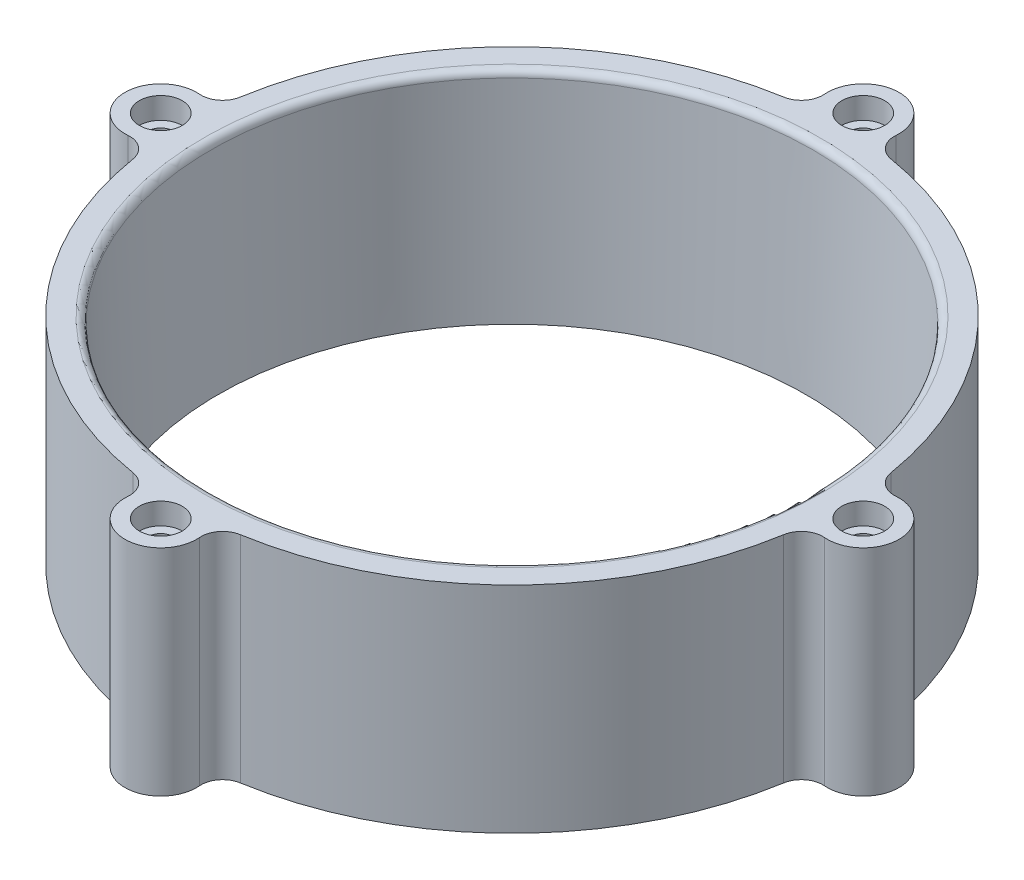
SolidWorks part; units mm, degrees
material "6061 合金"
ref_plane "前视基准面" through (0, 0, 0) normal (0, 0, 1) x (1, 0, 0)
ref_plane "上视基准面" through (0, 0, 0) normal (0, 1, 0) x (1, 0, 0)
ref_plane "右视基准面" through (0, 0, 0) normal (1, 0, 0) x (0, 0, -1)
sketch "草图1" plane through (0, 0, 0) normal (0, 1, 0) x (1, 0, 0)
  line L0 (-32, 0) -> (-32, 51.9) construction
  circle A0 centre (0, 0) radius 41
  circle A1 centre (0, 0) radius 49 construction
  circle A2 centre (0, 0) radius 32 construction
  circle A4 centre (0, 0) radius 41 construction
  circle A5 centre (0, 49) radius 1.7
  circle A6 centre (49, 0) radius 1.7
  circle A7 centre (0, -49) radius 1.7
  circle A8 centre (-49, 0) radius 1.7
  arc A36 (45.8367, 3.8722) -> (3.8722, 45.8367) centre (0, 0) ccw
  arc A37 (45.8367, -3.8722) -> (45.8367, 3.8722) centre (49, 0) ccw
  arc A38 (3.8722, 45.8367) -> (-3.8722, 45.8367) centre (0, 49) ccw
  arc A40 (-45.8367, 3.8722) -> (-45.8367, -3.8722) centre (-49, 0) ccw
  arc A41 (-3.8722, -45.8367) -> (3.8722, -45.8367) centre (0, -49) ccw
  arc A43 (-3.8722, 45.8367) -> (-45.8367, 3.8722) centre (0, 0) ccw
  arc A44 (-45.8367, -3.8722) -> (-3.8722, -45.8367) centre (0, 0) ccw
  arc A45 (3.8722, -45.8367) -> (45.8367, -3.8722) centre (0, 0) ccw
  dimension "D1" = 82
  dimension "D3" = 9
  dimension "D6" = 3.4
  dimension "D8" = 10
  dimension "D4" = 5
  dimension "D2" = 8
  dimension "D7" = 4
extrude "凸台-拉伸1" add sketch "草图1" along normal blind 30
fillet "圆角1" radius 3 8 edges at (-45.8367, 15, 3.8722) (-45.8367, 15, -3.8722) (3.8722, 15, -45.8367) (45.8367, 15, -3.8722) (45.8367, 15, 3.8722) (3.8722, 15, 45.8367) (-3.8722, 15, 45.8367) (-3.8722, 15, -45.8367)
sketch "草图2" plane through (0, 30, 0) normal (0, 1, 0) x (1, 0, 0)
  circle A0 centre (0, 49) radius 3
  circle A2 centre (-49, 0) radius 3
  circle A3 centre (0, -49) radius 3
  circle A4 centre (49, 0) radius 3
  dimension "D1" = 6
extrude "切除-拉伸1" cut sketch "草图2" against normal blind 3
draft "拔模1" type of draft neutral plane draft angle 2 faces to draft 1 face at (0, 30, 41) neutral plane through (0, 0, 24.5) neutral plane normal (0, -1, 0) reverse direction yes parameters "D1"=2
fillet "圆角4" radius 1 1 edges at (0, 30, 42.0476)
